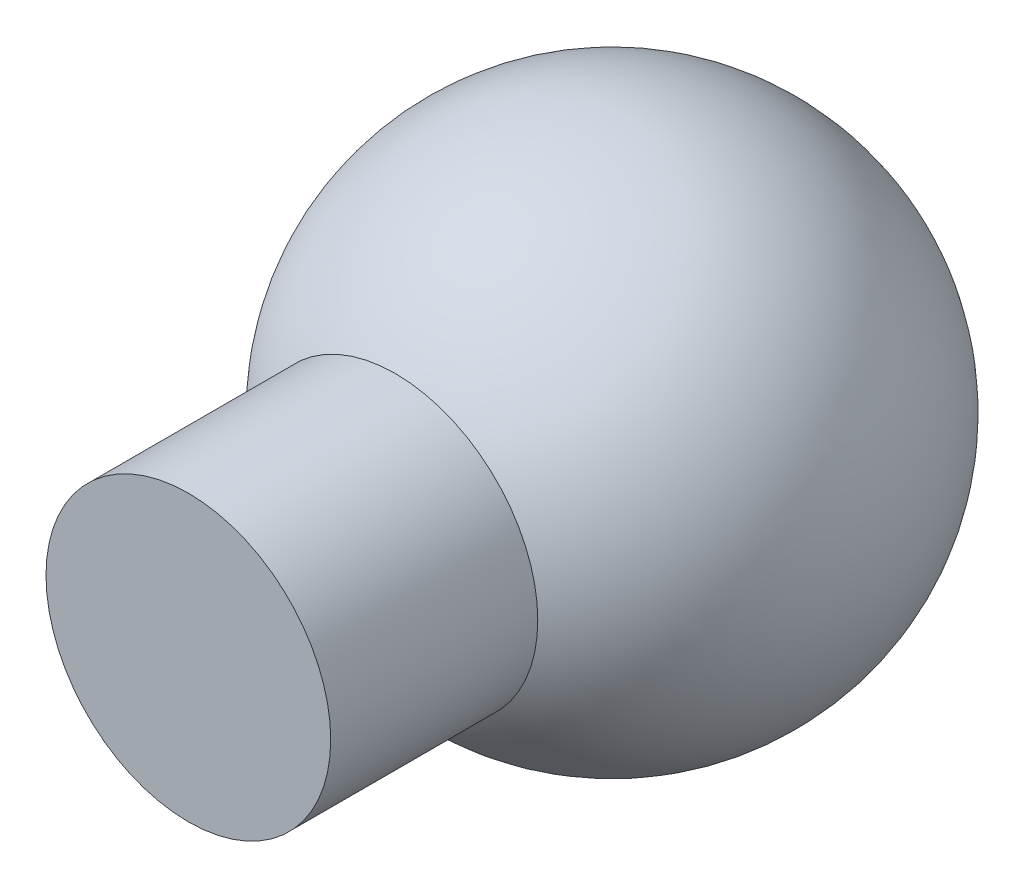
SolidWorks part; units mm, degrees
ref_plane "정면" through (0, 0, 0) normal (0, 0, 1) x (1, 0, 0)
ref_plane "윗면" through (0, 0, 0) normal (0, 1, 0) x (1, 0, 0)
ref_plane "우측면" through (0, 0, 0) normal (1, 0, 0) x (0, 0, -1)
sketch "스케치1" plane through (0, 0, 0) normal (0, 0, 1) x (1, 0, 0)
  circle A0 centre (0, 0) radius 5.5
extrude "보스-돌출1" add sketch "스케치1" along normal blind 15
sketch "스케치2" plane through (0, 0, 0) normal (0, 1, 0) x (1, 0, 0)
  line L0 (0, 18.3718) -> (0, 0)
  line L1 (0, 0) -> (-5.4693, 0)
  line L2 (5.5, 0) -> (-5.5, 0) construction
  arc A0 (0, 18.3718) -> (-5.4693, 0) centre (0, 8.3718) ccw
revolve "회전1" add sketch "스케치2" angle 360 about L0
sketch "스케치3" plane through (0, 0, 15) normal (0, 0, 1) x (1, 0, 0)
  circle A0 centre (0, 0) radius 7.1595
extrude "컷-돌출1" cut sketch "스케치3" against normal blind 7
